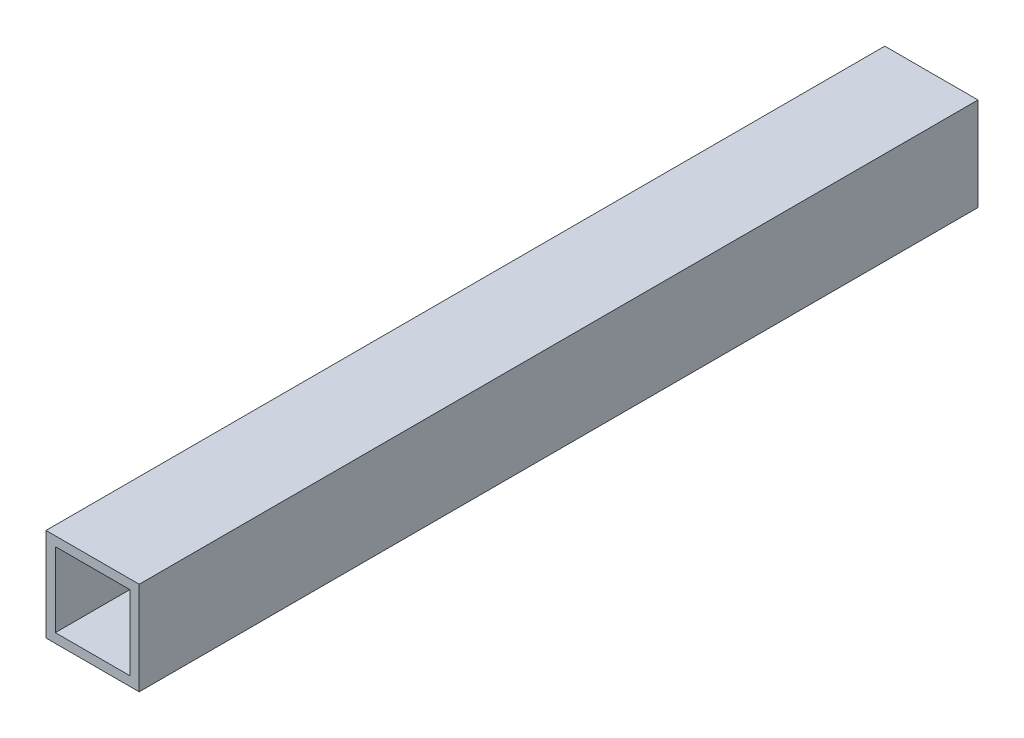
SolidWorks part; units mm, degrees
material "6063-O, Extruded Rod (SS)"
ref_plane "Front Plane" through (0, 0, 0) normal (0, 0, 1) x (1, 0, 0)
ref_plane "Top Plane" through (0, 0, 0) normal (0, 1, 0) x (1, 0, 0)
ref_plane "Right Plane" through (0, 0, 0) normal (1, 0, 0) x (0, 0, -1)
sketch "Sketch1" plane through (0, 0, 0) normal (0, 0, 1) x (1, 0, 0)
  line L0 (-10.16, 10.16) -> (10.16, 10.16)
  line L1 (-12.7, -12.7) -> (12.7, -12.7)
  line L2 (-12.7, -12.7) -> (-12.7, 12.7)
  line L3 (-12.7, 12.7) -> (12.7, 12.7)
  line L4 (12.7, -12.7) -> (12.7, 12.7)
  line L5 (-12.7, -12.7) -> (12.7, 12.7) construction
  line L6 (-12.7, 12.7) -> (12.7, -12.7) construction
  line L7 (10.16, -10.16) -> (10.16, 10.16)
  line L8 (-10.16, -10.16) -> (10.16, -10.16)
  line L9 (-10.16, -10.16) -> (-10.16, 10.16)
  point P0 (0, 0)
  dimension "D1" = 25.4
  dimension "D2" = 25.4
  dimension "D3" = 2.54
extrude "Boss-Extrude1" add sketch "Sketch1" along normal mid plane 228.6
